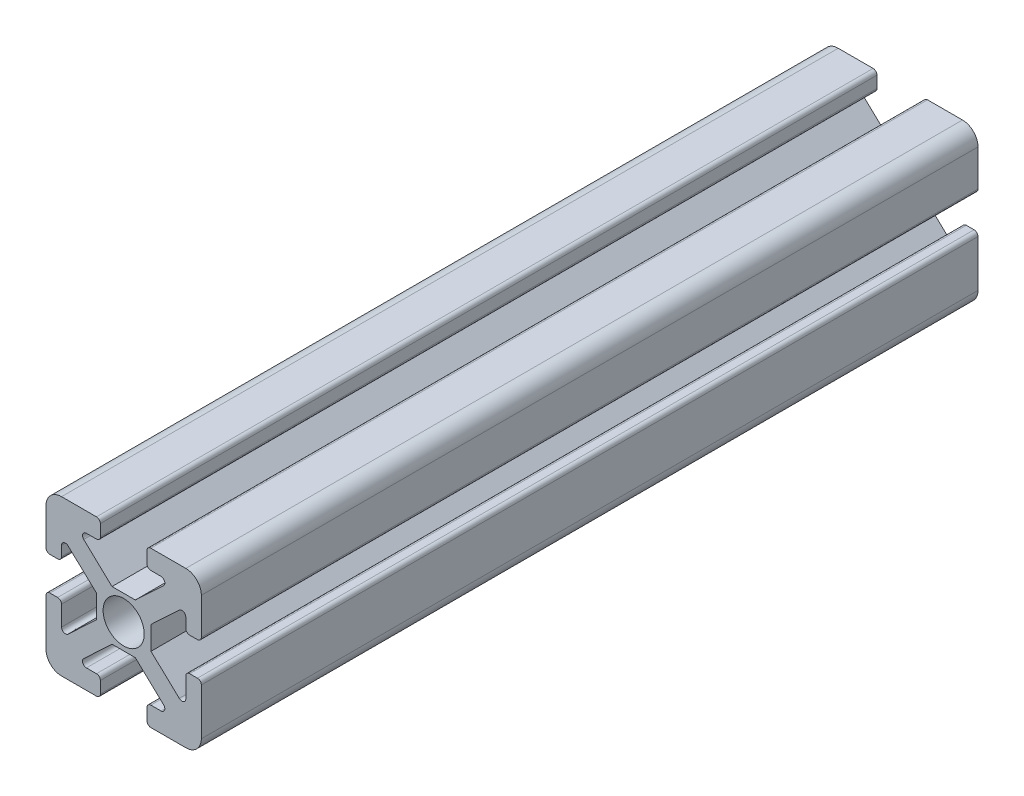
SolidWorks part; units mm, degrees
ref_plane "Front Plane" through (0, 0, 0) normal (0, 0, 1) x (1, 0, 0)
ref_plane "Top Plane" through (0, 0, 0) normal (0, 1, 0) x (1, 0, 0)
ref_plane "Right Plane" through (0, 0, 0) normal (1, 0, 0) x (0, 0, -1)
sketch "Sketch1" plane through (0, 0, 0) normal (0, 0, 1) x (1, 0, 0)
  line L0 (0, 2) -> (0, 8.0075)
  line L1 (2, 20) -> (6.5, 20)
  line L2 (20, 18) -> (20, 13.3075)
  line L3 (18, 0) -> (13.5, 0)
  line L4 (10, 0.2965) -> (10, 6.7965) construction
  line L5 (-0.015, 9.9158) -> (6.485, 9.9158) construction
  line L6 (18.5, 8.5075) -> (19.5, 8.5075)
  line L7 (18.5, 12.8075) -> (19.5, 12.8075)
  line L8 (13, 19.5) -> (13, 18.0175)
  line L9 (7, 19.5) -> (7, 18.0175)
  line L10 (2, 14.5732) -> (2, 13.3075)
  line L11 (5.2, 2.5071) -> (6.5, 2.5071)
  line L12 (18, 5.4513) -> (18, 8.0075)
  line L13 (14.8, 17.5175) -> (13.5, 17.5175)
  line L14 (1.5, 12.8075) -> (0.5, 12.8075)
  line L15 (13.5, 20) -> (18, 20)
  line L16 (6.5, 17.5175) -> (5.2, 17.5175)
  line L17 (20, 8.0075) -> (20, 2)
  line L18 (18, 13.3075) -> (18, 14.5732)
  line L19 (0, 13.3075) -> (0, 18)
  line L20 (2, 8.0075) -> (2, 5.4513)
  line L21 (6.5, 0) -> (2, 0)
  line L22 (13.5, 2.5071) -> (14.8, 2.5071)
  line L23 (1.5, 8.5075) -> (0.5, 8.5075)
  line L24 (13, 0.5) -> (13, 2.0071)
  line L25 (7, 2.0071) -> (7, 0.5)
  line L26 (17.1575, 14.9375) -> (13.515, 11.5123)
  line L27 (15.1425, 16.6533) -> (11.5, 13.228)
  line L28 (4.8575, 16.6533) -> (8.5, 13.228)
  line L29 (2.8425, 14.9375) -> (6.485, 11.5123)
  line L30 (13.515, 8.5123) -> (17.1575, 5.0871)
  line L31 (8.5, 6.7965) -> (11.5, 6.7965)
  line L32 (6.485, 8.5123) -> (6.485, 11.5123)
  line L33 (8.5, 13.228) -> (11.5, 13.228)
  line L34 (13.515, 8.5123) -> (13.515, 11.5123)
  line L37 (6.485, 8.5123) -> (2.8425, 5.0871)
  line L38 (13.515, 9.9158) -> (19.985, 9.9158) construction
  line L39 (11.5, 6.7965) -> (15.1425, 3.3713)
  line L41 (8.5, 6.7965) -> (4.8575, 3.3713)
  line L43 (10.0737, 13.228) -> (10.0737, 19.728) construction
  circle A0 centre (10, 10) radius 2.65
  arc A1 (0, 18) -> (2, 20) centre (2, 18) cw
  arc A2 (0, 2) -> (2, 0) centre (2, 2) ccw
  arc A3 (20, 2) -> (18, 0) centre (18, 2) cw
  arc A4 (18, 20) -> (20, 18) centre (18, 18) cw
  arc A5 (19.5, 8.5075) -> (20, 8.0075) centre (19.5, 8.0075) cw
  arc A6 (0.5, 8.5075) -> (0, 8.0075) centre (0.5, 8.0075) ccw
  arc A7 (0.5, 12.8075) -> (0, 13.3075) centre (0.5, 13.3075) cw
  arc A8 (13, 19.5) -> (13.5, 20) centre (13.5, 19.5) cw
  arc A9 (7, 19.5) -> (6.5, 20) centre (6.5, 19.5) ccw
  arc A10 (18, 8.0075) -> (18.5, 8.5075) centre (18.5, 8.0075) cw
  arc A11 (18.5, 12.8075) -> (18, 13.3075) centre (18.5, 13.3075) cw
  arc A12 (19.5, 12.8075) -> (20, 13.3075) centre (19.5, 13.3075) ccw
  arc A13 (7, 18.0175) -> (6.5, 17.5175) centre (6.5, 18.0175) cw
  arc A14 (13.5, 17.5175) -> (13, 18.0175) centre (13.5, 18.0175) cw
  arc A15 (2, 13.3075) -> (1.5, 12.8075) centre (1.5, 13.3075) cw
  arc A16 (2, 8.0075) -> (1.5, 8.5075) centre (1.5, 8.0075) ccw
  arc A17 (6.5, 2.5071) -> (7, 2.0071) centre (6.5, 2.0071) cw
  arc A18 (7, 0.5) -> (6.5, 0) centre (6.5, 0.5) cw
  arc A19 (13.5, 2.5071) -> (13, 2.0071) centre (13.5, 2.0071) ccw
  arc A20 (13, 0.5) -> (13.5, 0) centre (13.5, 0.5) ccw
  arc A21 (17.1575, 5.0871) -> (18, 5.4513) centre (17.5, 5.4513) ccw
  arc A22 (14.8, 2.5071) -> (15.1425, 3.3713) centre (14.8, 3.0071) ccw
  arc A23 (5.2, 2.5071) -> (4.8575, 3.3713) centre (5.2, 3.0071) cw
  arc A24 (2, 5.4513) -> (2.8425, 5.0871) centre (2.5, 5.4513) ccw
  arc A25 (2, 14.5732) -> (2.8425, 14.9375) centre (2.5, 14.5732) cw
  arc A26 (4.8575, 16.6533) -> (5.2, 17.5175) centre (5.2, 17.0175) cw
  arc A27 (17.1575, 14.9375) -> (18, 14.5732) centre (17.5, 14.5732) cw
  arc A28 (14.8, 17.5175) -> (15.1425, 16.6533) centre (14.8, 17.0175) cw
  point P13 (0, 20)
  point P16 (0, 0)
  point P19 (20, 0)
  point P42 (20, 8.5075)
  point P45 (0, 8.5075)
  point P48 (0, 12.8075)
  point P51 (13, 20)
  point P64 (2, 12.8075)
  point P67 (2, 8.5075)
  point P70 (7, 2.5071)
  point P75 (13, 2.5071)
  dimension "D3" = 2
  dimension "D8" = 0.5
  dimension "D4" = 0.5
  dimension "D5" = 0.5
  dimension "D6" = 0.5
  dimension "D7" = 0.5
  dimension "D9" = 5.3
  dimension "D12" = 2
  dimension "D13" = 5
  dimension "D14" = 1.3
  dimension "D1" = 20
  dimension "D2" = 20
  dimension "D10" = 3
  dimension "D11" = 2
  dimension "D15" = 1.3
  dimension "D16" = 1.3
  dimension "D17" = 6
  dimension "D18" = 5.3
  dimension "D19" = 10
  dimension "D20" = 10
  dimension "D21" = 133.239
extrude "Boss-Extrude2" add sketch "Sketch1" along normal blind 100
